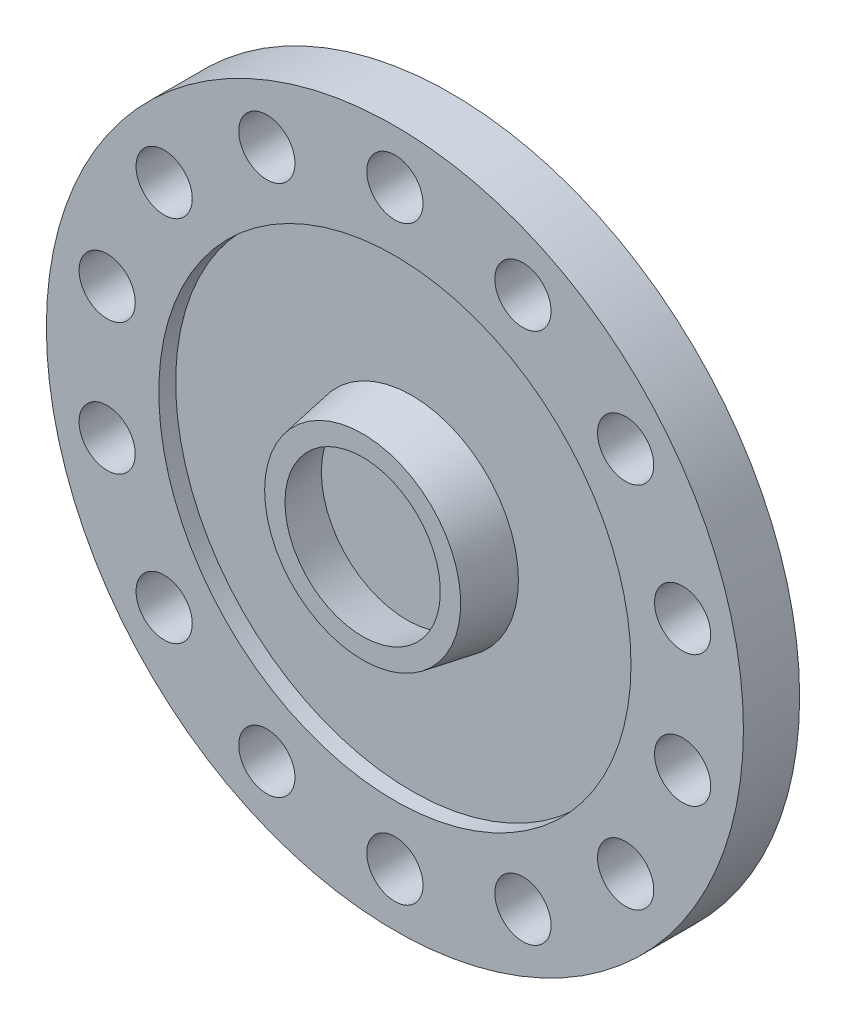
SolidWorks part; units mm, degrees
ref_plane "Front Plane" through (0, 0, 0) normal (0, 0, 1) x (1, 0, 0)
ref_plane "Top Plane" through (0, 0, 0) normal (0, 1, 0) x (1, 0, 0)
ref_plane "Right Plane" through (0, 0, 0) normal (1, 0, 0) x (0, 0, -1)
sketch "Sketch1" plane through (0, 0, 0) normal (0, 0, 1) x (1, 0, 0)
  line L0 (0, 0) -> (0, 62) construction
  line L1 (0, 43) -> (0, 62) construction
  circle A0 centre (0, 0) radius 62
  circle A1 centre (0, 0) radius 43
  circle A2 centre (0, 52.5) radius 5
  circle A3 centre (22.7789, 47.3009) radius 5
  circle A4 centre (41.0462, 32.7332) radius 5
  circle A5 centre (51.1837, 11.6823) radius 5
  circle A6 centre (51.1837, -11.6823) radius 5
  circle A7 centre (41.0462, -32.7332) radius 5
  circle A8 centre (22.7789, -47.3009) radius 5
  circle A9 centre (0, -52.5) radius 5
  circle A10 centre (-22.7789, -47.3009) radius 5
  circle A11 centre (-41.0462, -32.7332) radius 5
  circle A12 centre (-51.1837, -11.6823) radius 5
  circle A13 centre (-51.1837, 11.6823) radius 5
  circle A14 centre (-41.0462, 32.7332) radius 5
  circle A15 centre (-22.7789, 47.3009) radius 5
  point P36 (0, 0)
  dimension "D1" = 14
extrude "Boss-Extrude2" add sketch "Sketch1" along normal blind 10 contours A1 | A0 A15 A14 A13 A12 A11 A10 A9 A8 A7 A6 A5 A4 A3 A2 A1
sketch "Sketch2" plane through (0, 0, 10) normal (0, 0, 1) x (1, 0, 0)
  circle A0 centre (0, 0) radius 42
extrude "Cut-Extrude1" cut sketch "Sketch2" against normal blind 3
sketch "Sketch3" plane through (0, 0, 7) normal (0, 0, 1) x (1, 0, 0)
  circle A0 centre (0, 0) radius 10.4045
  point P3 (0, 0)
sketch "Sketch5" plane through (0, 0, 0) normal (0, 1, 0) x (1, 0, 0)
  line L0 (0, 0) -> (0, -16) construction
  line L1 (0, -6.8708) -> (-19, -6.8708) construction
  line L2 (-19, -6.8708) -> (-19, -15.6459) construction
  line L3 (0, -6.8708) -> (-19, -6.8708)
  line L4 (-19, -6.8708) -> (-17.4372, -15.7341)
  line L11 (-15.2063, -7.8708) -> (0, -7.8708)
  line L14 (-17.4372, -15.7341) -> (-13.8198, -15.7341)
  line L20 (0, -7.8708) -> (0, -6.8708)
  line L22 (-15.2063, -7.8708) -> (-13.8198, -15.7341)
revolve "Revolve1" add sketch "Sketch5" angle 360 about L0
sketch "Sketch6" plane through (0, 0, 7) normal (0, 0, 1) x (1, 0, 0)
  line L0 (0, 42) -> (0, -42) construction
  line L1 (42, 0) -> (-42, 0) construction
  line L2 (0, 0) -> (-29.6985, 29.6985) construction
  line L3 (0, 0) -> (29.6985, 29.6985) construction
  line L4 (0, 0) -> (29.6985, -29.6985) construction
  line L5 (0, 0) -> (-29.6985, -29.6985) construction
  circle A0 centre (0, 0) radius 42 construction
  circle A1 centre (0, 0) radius 42 construction
  point P18 (0, 0)
  dimension "D1" = 4
